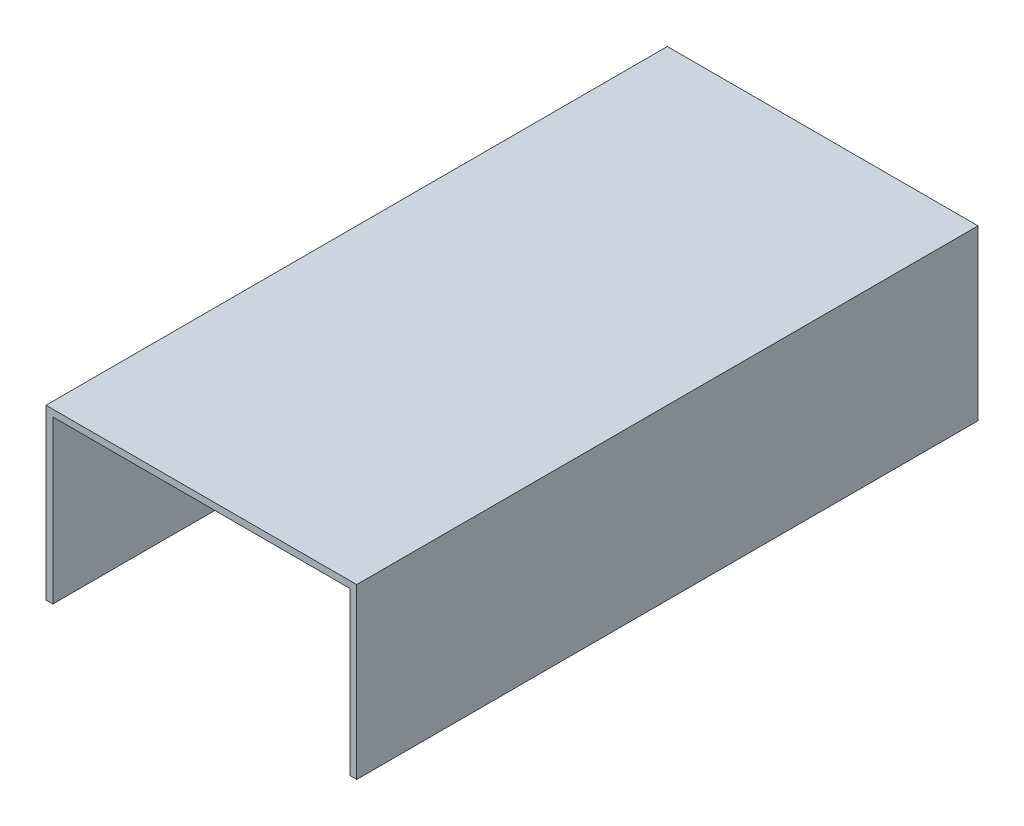
SolidWorks part; units mm, degrees
material "Glass"
ref_plane "Front Plane" through (0, 0, 0) normal (0, 0, 1) x (1, 0, 0)
ref_plane "Top Plane" through (0, 0, 0) normal (0, 1, 0) x (1, 0, 0)
ref_plane "Right Plane" through (0, 0, 0) normal (1, 0, 0) x (0, 0, -1)
sketch "Sketch1" plane through (0, 0, 0) normal (0, 0, 1) x (1, 0, 0)
  line L1 (0, 0) -> (146.05, 0)
  line L2 (0, 0) -> (0, 79.375)
  line L3 (0, 79.375) -> (146.05, 79.375)
  line L4 (146.05, 0) -> (146.05, 79.375)
  line L5 (3.175, 0) -> (142.875, 0)
  line L6 (3.175, 0) -> (3.175, 76.2)
  line L7 (3.175, 76.2) -> (142.875, 76.2)
  line L8 (142.875, 0) -> (142.875, 76.2)
  dimension "D1" = 139.7
  dimension "D2" = 76.2
  dimension "D3" = 0
  dimension "D4" = 3.175
  dimension "D5" = 3.175
  dimension "D6" = 3.175
extrude "Boss-Extrude1" add sketch "Sketch1" along normal blind 292.1 contours L8 L1 L4 L3 L2 L6 L7
